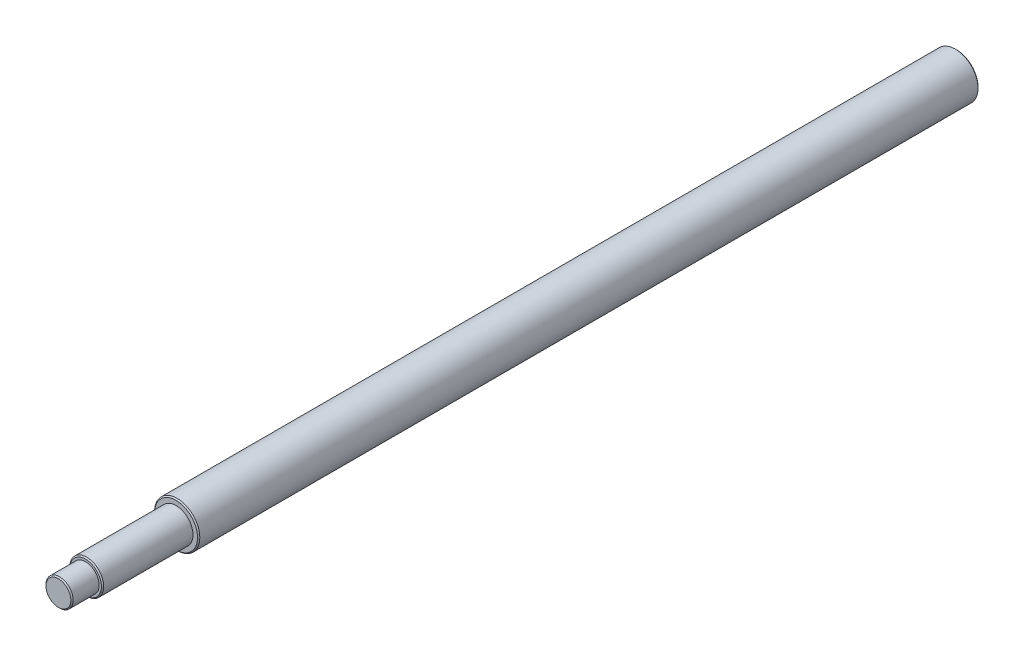
SolidWorks part; units mm, degrees
material "Chrome Stainless Steel"
ref_plane "Front Plane" through (0, 0, 0) normal (0, 0, 1) x (1, 0, 0)
ref_plane "Top Plane" through (0, 0, 0) normal (0, 1, 0) x (1, 0, 0)
ref_plane "Right Plane" through (0, 0, 0) normal (1, 0, 0) x (0, 0, -1)
sketch "Sketch1" plane through (0, 0, 0) normal (0, 0, 1) x (1, 0, 0)
  circle A0 centre (0, 0) radius 10
  dimension "D1" = 20
extrude "Boss-Extrude1" add sketch "Sketch1" along normal mid plane 345
cosmetic thread "Cosmetic Thread1" parameters "D2"=17
sketch "Sketch4" plane through (0, 0, 172.5) normal (0, 0, 1) x (1, 0, 0)
  circle A0 centre (0, 0) radius 7.5
  dimension "D1" = 15
extrude "Boss-Extrude2" add sketch "Sketch4" along normal blind 40
cosmetic thread "Cosmetic Thread2" parameters "D1"=15, "D2"=13
sketch "Sketch5" plane through (0, 0, 212.5) normal (0, 0, 1) x (1, 0, 0)
  circle A0 centre (0, 0) radius 6
  dimension "D1" = 12
extrude "Boss-Extrude3" add sketch "Sketch5" along normal blind 12
chamfer "Chamfer1" distance 0.5 angle 45 4 edges at (6, 0, 224.5) (10, 0, -172.5) (10, 0, 172.5) (7.5, 0, 212.5)
